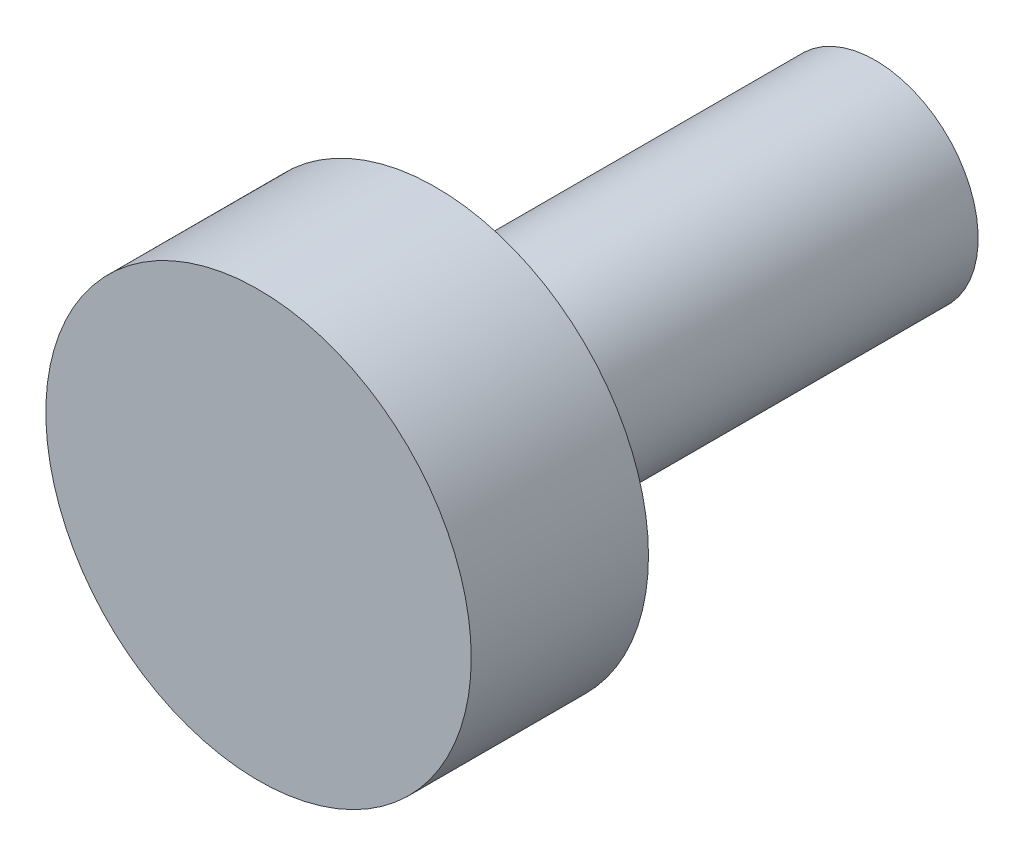
SolidWorks part; units mm, degrees
material "Plain Carbon Steel"
ref_plane "Front Plane" through (0, 0, 0) normal (0, 0, 1) x (1, 0, 0)
ref_plane "Top Plane" through (0, 0, 0) normal (0, 1, 0) x (1, 0, 0)
ref_plane "Right Plane" through (0, 0, 0) normal (1, 0, 0) x (0, 0, -1)
sketch "Sketch1" plane through (0, 0, 0) normal (0, 0, 1) x (1, 0, 0)
  circle A0 centre (0, 0) radius 3
  dimension "D1" = 6
extrude "Boss-Extrude1" add sketch "Sketch1" along normal blind 2.5 from offset 0
sketch "Sketch2" plane through (0, 0, 0) normal (0, 0, 1) x (1, 0, 0)
  circle A0 centre (0, 0) radius 1.45
  dimension "D1" = 2.9
extrude "Boss-Extrude2" add sketch "Sketch2" along normal blind 6.2 from offset 6.2
